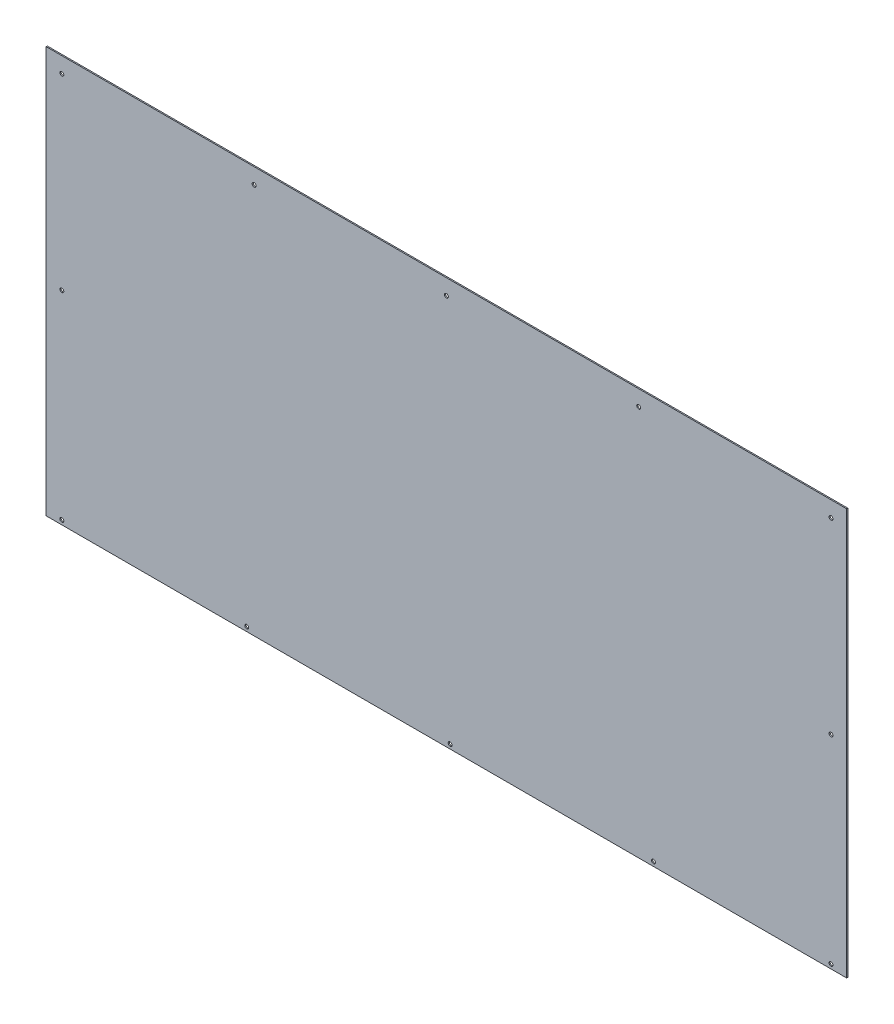
SolidWorks part; units mm, degrees
ref_plane "Alzado" through (0, 0, 0) normal (0, 0, 1) x (1, 0, 0)
ref_plane "Planta" through (0, 0, 0) normal (0, 1, 0) x (1, 0, 0)
ref_plane "Vista lateral" through (0, 0, 0) normal (1, 0, 0) x (0, 0, -1)
sketch "Croquis1" plane through (0, 0, 0) normal (0, 0, 1) x (1, 0, 0)
  line L1 (-650, 330) -> (650, 330)
  line L2 (-650, 330) -> (-650, -330)
  line L3 (-650, -330) -> (650, -330)
  line L4 (650, 330) -> (650, -330)
  line L5 (-650, 330) -> (650, -330) construction
  line L6 (-650, -330) -> (650, 330) construction
  point P0 (0, 0)
  dimension "D1" = 660
  dimension "D2" = 1300
extrude "Saliente-Extruir1" add sketch "Croquis1" along normal blind 1.9
sketch "Croquis2" plane through (0, 0, 1.9) normal (0, 0, 1) x (1, 0, 0)
  line L0 (650, 330) -> (-650, 330) construction
  line L1 (-624.6, -304.6) -> (624.6, -304.6) construction
  line L2 (-624.6, -304.6) -> (-624.6, 304.6) construction
  line L3 (-624.6, 304.6) -> (624.6, 304.6) construction
  line L4 (624.6, -304.6) -> (624.6, 304.6) construction
  line L5 (-624.6, -304.6) -> (624.6, 304.6) construction
  line L6 (-624.6, 304.6) -> (624.6, -304.6) construction
  line L7 (-650, 330) -> (-650, -330) construction
  line L8 (0, 0) -> (0, 304.6) construction
  line L9 (0, 0) -> (159.2342, 0) construction
  line L10 (-624.6, 304.6) -> (0, 304.6) construction
  line L11 (0, 304.6) -> (-312.3, 304.6) construction
  line L12 (0, 304.6) -> (624.6, 304.6) construction
  line L13 (624.6, 304.6) -> (312.3, 304.6) construction
  line L14 (-624.6, 0) -> (0, 0) construction
  line L15 (-624.6, -330) -> (-624.6, -323) construction
  line L16 (-650, -330) -> (650, -330) construction
  circle A0 centre (-624.6, 304.6) radius 3.175
  circle A1 centre (0, 304.6) radius 3.175
  circle A2 centre (624.6, 304.6) radius 3.175
  circle A3 centre (-312.3, 304.6) radius 3.175
  circle A4 centre (312.3, 304.6) radius 3.175
  circle A5 centre (-624.6, 0) radius 3.175
  circle A6 centre (624.6, 0) radius 3.175
  circle A7 centre (-624.6, -323) radius 3.175
  circle A8 centre (624.6, -323) radius 3.175
  point P0 (0, 0)
  dimension "D3" = 6.35
  dimension "D4" = 6.35
  dimension "D5" = 6.35
  dimension "D6" = 6.35
  dimension "D7" = 6.35
  dimension "D8" = 6.35
  dimension "D1" = 25.4
  dimension "D2" = 25.4
  dimension "D9" = 7
extrude "Cortar-Extruir2" cut sketch "Croquis2" against normal blind 6.35
sketch "Croquis4" plane through (0, 0, 0) normal (0, 0, -1) x (-1, 0, 0)
  line L0 (294.3, -337) -> (294.3, -320.391) construction
  line L1 (624.6, -323) -> (-71.6985, -317.5) construction
  line L2 (599.2, -317.5) -> (-599.2, -317.5) construction
  line L3 (294.3, -320.391) -> (324.3, -320.628) construction
  line L4 (-36, -323) -> (-36, -317.782) construction
  line L5 (-36, -317.782) -> (-6, -318.0189) construction
  line L6 (-366.3, -337) -> (-366.3, -315.173) construction
  line L7 (-366.3, -315.173) -> (-336.3, -315.4099) construction
  line L8 (-624.6, 307.775) -> (-624.6, 330) construction
  line L9 (-650, 330) -> (650, 330) construction
  line L10 (624.6, 304.6) -> (624.6, 330) construction
  line L11 (624.6, 330) -> (624.6, -323) construction
  line L12 (624.6, -323) -> (-624.6, -323) construction
  line L13 (324.3, -320.628) -> (324.3, -323) construction
  line L14 (-6, -318.0189) -> (-6, -323) construction
  line L15 (-336.3, -315.4099) -> (-336.3, -323) construction
  circle A0 centre (324.3, -320.628) radius 3.175 construction
  circle A1 centre (-6, -318.0189) radius 3.175 construction
  circle A2 centre (-336.3, -315.4099) radius 3.175 construction
  circle A3 centre (-624.6, 304.6) radius 3.175 construction
  circle A4 centre (324.3, -323) radius 3.175
  circle A5 centre (-6, -323) radius 3.175
  circle A6 centre (-336.3, -323) radius 3.175
  point P16 (-36, -320.391)
  dimension "D4" = 6.35
  dimension "D5" = 6.35
  dimension "D6" = 6.35
  dimension "D7" = 6.35
  dimension "D8" = 6.35
  dimension "D9" = 6.35
  dimension "D1" = 30
  dimension "D2" = 30
  dimension "D3" = 30
extrude "Cortar-Extruir3" cut sketch "Croquis4" against normal blind 10
